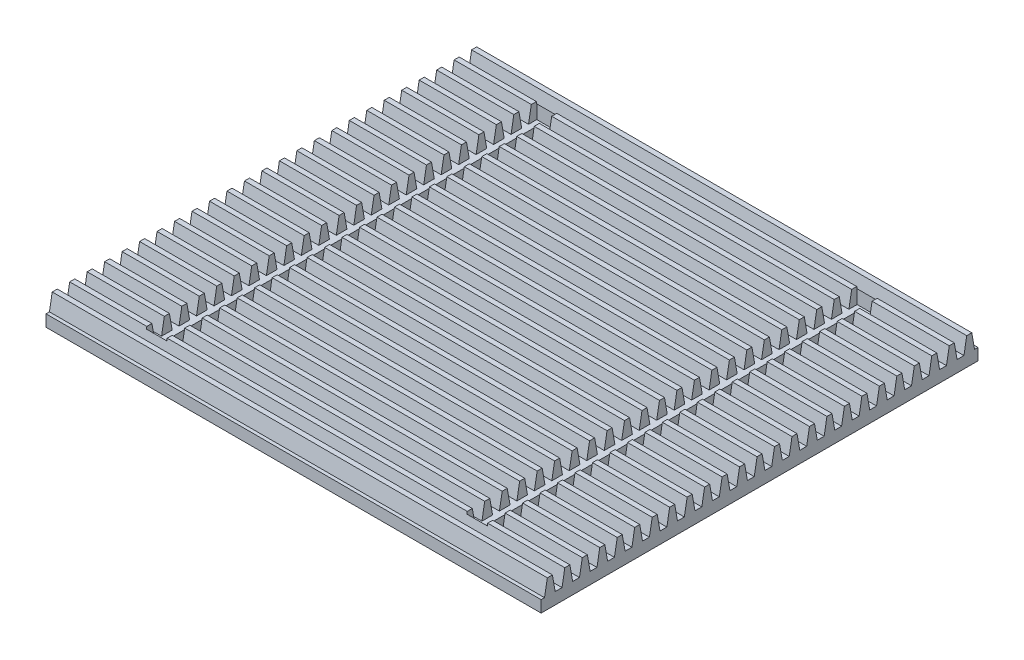
SolidWorks part; units mm, degrees
ref_plane "Front Plane" through (0, 0, 0) normal (0, 0, 1) x (1, 0, 0)
ref_plane "Top Plane" through (0, 0, 0) normal (0, 1, 0) x (1, 0, 0)
ref_plane "Right Plane" through (0, 0, 0) normal (1, 0, 0) x (0, 0, -1)
sketch "Sketch1" plane through (0, 0, 0) normal (1, 0, 0) x (0, 0, -1)
  line L0 (0, 0) -> (6, 0)
  line L1 (6, 0) -> (6, 4)
  line L2 (0, 4) -> (1.1735, 4)
  line L3 (1.1735, 4) -> (2.1317, 9.434)
  line L4 (2.1317, 9.434) -> (3.8683, 9.434)
  line L5 (0, 0) -> (0, 4)
  line L6 (3.8683, 9.434) -> (4.8265, 4)
  line L7 (4.8265, 4) -> (6, 4)
  dimension "D1" = 6
  dimension "D2" = 4
  dimension "D3" = 100
  dimension "D4" = 100
extrude "Boss-Extrude1" add sketch "Sketch1" along normal blind 170
pattern_linear "LPattern1" count 25 spacing 6 along (0, 0, -1) of "Boss-Extrude1"
sketch "Sketch2" plane through (0, 0, 0) normal (0, -1, 0) x (1, 0, 0)
  line L0 (0, 0) -> (0, -150) construction
  line L1 (28.5, -10) -> (31.5, -10)
  line L2 (28.5, -10) -> (28.5, -140)
  line L3 (28.5, -140) -> (31.5, -140)
  line L4 (31.5, -10) -> (31.5, -140)
  line L5 (170, 0) -> (0, 0) construction
  line L6 (170, -150) -> (0, -150) construction
  dimension "D1" = 3
  dimension "D2" = 28.5
  dimension "D3" = 10
  dimension "D4" = 10
extrude "Cut-Extrude1" cut sketch "Sketch2" against normal blind 10
sketch "Sketch3" plane through (0, 4, 0) normal (0, 1, 0) x (1, 0, 0)
  line L1 (33.5, 142) -> (26.5, 142)
  line L2 (33.5, 142) -> (33.5, 8)
  line L3 (33.5, 8) -> (26.5, 8)
  line L4 (26.5, 142) -> (26.5, 8)
  line L7 (28.5, 140) -> (31.5, 140) construction
  line L8 (31.5, 10) -> (28.5, 10) construction
  line L9 (31.5, 13.1735) -> (31.5, 10.8265) construction
  line L10 (28.5, 10.8265) -> (28.5, 13.1735) construction
  point P8 (0, 0)
  point P9 (0, 0)
  dimension "D1" = 2
  dimension "D2" = 2
  dimension "D3" = 2
  dimension "D4" = 2
extrude "Cut-Extrude3" cut sketch "Sketch3" along normal up to surface (5.434 mm away) up to face at (100.75, 9.434, -63)
ref_plane "Plane1" through (85, 0, 0) normal (1, 0, 0) x (0, 0, -1)
mirror "Mirror1" about plane through (85, 0, 0) normal (1, 0, 0) of "Cut-Extrude3", "Cut-Extrude1"
